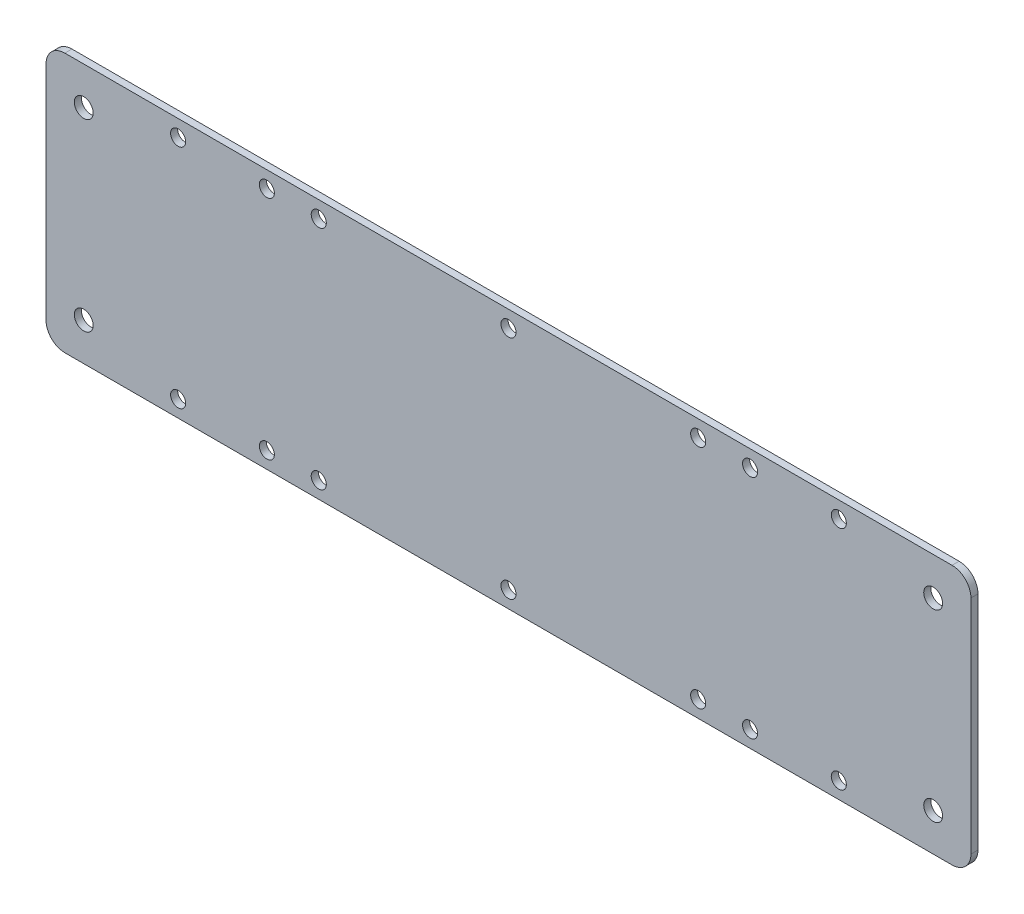
SolidWorks part; units mm, degrees
ref_plane "Plan de face" through (0, 0, 0) normal (0, 0, 1) x (1, 0, 0)
ref_plane "Plan de dessus" through (0, 0, 0) normal (0, 1, 0) x (1, 0, 0)
ref_plane "Plan de droite" through (0, 0, 0) normal (1, 0, 0) x (0, 0, -1)
sketch "Esquisse1" plane through (0, 0, 0) normal (0, 0, 1) x (1, 0, 0)
  line L1 (-98, 27.5) -> (98, 27.5)
  line L2 (-98, 27.5) -> (-98, -27.5)
  line L3 (-98, -27.5) -> (98, -27.5)
  line L4 (98, 27.5) -> (98, -27.5)
  line L5 (-98, 27.5) -> (98, -27.5) construction
  line L6 (-98, -27.5) -> (98, 27.5) construction
  point P0 (0, 0)
  point P6 (98, 0)
  dimension "D1" = 196
  dimension "D2" = 55
extrude "Boss.-Extru.1" add sketch "Esquisse1" along normal blind 1.5 contours L1 L4 L3 L2
fillet "Congé1" radius 4 4 edges at (98, -27.5, 0.75) (98, 27.5, 0.75) (-98, -27.5, 0.75) (-98, 27.5, 0.75)
sketch "Esquisse2" plane through (0, 0, 1.5) normal (0, 0, 1) x (1, 0, 0)
  line L0 (-94, 27.5) -> (94, 27.5) construction
  line L1 (-90, 19.5) -> (90, 19.5) construction
  line L2 (-90, 19.5) -> (-90, -19.5) construction
  line L3 (-90, -19.5) -> (90, -19.5) construction
  line L4 (90, 19.5) -> (90, -19.5) construction
  line L5 (-90, 19.5) -> (90, -19.5) construction
  line L6 (-90, -19.5) -> (90, 19.5) construction
  circle A1 centre (-90, 19.5) radius 2
  circle A2 centre (-90, -19.5) radius 2
  circle A3 centre (90, 19.5) radius 2
  circle A4 centre (90, -19.5) radius 2
  point P0 (0, 0)
  dimension "D3" = 4
  dimension "D1" = 180
  dimension "D2" = 8
extrude "Enlèv. mat.-Extru.1" cut sketch "Esquisse2" against normal through all
sketch "Esquisse3" plane through (0, 0, 1.5) normal (0, 0, 1) x (1, 0, 0)
  line L1 (-51.2, 24) -> (-40.2, 24) construction
  line L2 (-51.2, 24) -> (-51.2, -24) construction
  line L3 (-51.2, -24) -> (-40.2, -24) construction
  line L4 (-40.2, 24) -> (-40.2, -24) construction
  line L5 (-51.2, 24) -> (-40.2, -24) construction
  line L6 (-51.2, -24) -> (-40.2, 24) construction
  line L7 (0, 0) -> (0, 18.8988) construction
  line L8 (-45.7, 0) -> (0, 0) construction
  circle A0 centre (-51.2, 24) radius 1.6
  circle A1 centre (-40.2, 24) radius 1.6
  circle A2 centre (-40.2, -24) radius 1.6
  circle A3 centre (-51.2, -24) radius 1.6
  circle A4 centre (40.2, -24) radius 1.6
  circle A5 centre (51.2, -24) radius 1.6
  circle A6 centre (51.2, 24) radius 1.6
  circle A7 centre (40.2, 24) radius 1.6
  point P4 (-45.7, 0)
  dimension "D5" = 3.2
  dimension "D1" = 48
  dimension "D2" = 11
  dimension "D3" = 40.2
extrude "Enlèv. mat.-Extru.2" cut sketch "Esquisse3" against normal up to next
sketch "Esquisse4" plane through (0, 0, 1.5) normal (0, 0, 1) x (1, 0, 0)
  line L0 (-70, 24) -> (0, 24) construction
  line L1 (0, 24) -> (70, 24) construction
  line L2 (0, 24) -> (0, 0) construction
  line L3 (0, 0) -> (32.641, 0) construction
  line L4 (-94, 27.5) -> (94, 27.5) construction
  circle A0 centre (-70, 24) radius 1.6
  circle A1 centre (0, 24) radius 1.6
  circle A2 centre (70, 24) radius 1.6
  circle A3 centre (70, -24) radius 1.6
  circle A4 centre (0, -24) radius 1.6
  circle A5 centre (-70, -24) radius 1.6
  dimension "D1" = 3.2
  dimension "D2" = 70
  dimension "D3" = 3.5
extrude "Enlèv. mat.-Extru.3" cut sketch "Esquisse4" against normal up to next
